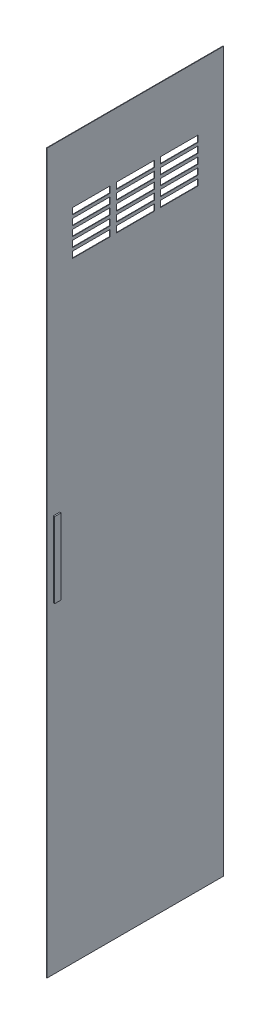
SolidWorks part; units mm, degrees
ref_plane "Front Plane" through (0, 0, 0) normal (0, 0, 1) x (1, 0, 0)
ref_plane "Top Plane" through (0, 0, 0) normal (0, 1, 0) x (1, 0, 0)
ref_plane "Right Plane" through (0, 0, 0) normal (1, 0, 0) x (0, 0, -1)
sketch "Sketch1" plane through (0, 0, 0) normal (1, 0, 0) x (0, 0, -1)
  line L1 (177.8, 725.551) -> (-177.8, 725.551)
  line L2 (177.8, 725.551) -> (177.8, -725.551)
  line L3 (177.8, -725.551) -> (-177.8, -725.551)
  line L4 (-177.8, 725.551) -> (-177.8, -725.551)
  line L5 (177.8, 725.551) -> (-177.8, -725.551) construction
  line L6 (177.8, -725.551) -> (-177.8, 725.551) construction
  point P0 (0, 0)
  dimension "D1" = 355.6
  dimension "D2" = 1451.102
extrude "Boss-Extrude1" add sketch "Sketch1" along normal blind 1 contours L4 L3 L2 L1
sketch "Sketch2" plane through (1, 0, 0) normal (1, 0, 0) x (0, 0, -1)
  line L0 (0, 0) -> (0, 725.551) construction
  line L1 (177.8, 725.551) -> (-177.8, 725.551) construction
  line L2 (0, 362.7755) -> (-177.8, 362.7755) construction
  line L3 (-177.8, 725.551) -> (-177.8, -725.551) construction
  line L4 (0, 362.7755) -> (177.8, 362.7755) construction
  line L5 (177.8, 725.551) -> (177.8, -725.551) construction
  line L6 (0, 725.551) -> (0, 362.7755) construction
  line L7 (-177.8, 725.551) -> (-177.8, 362.7755) construction
  line L8 (-177.8, 544.1632) -> (177.8, 544.1632) construction
  line L9 (177.8, 544.1632) -> (177.8, 725.551) construction
  line L10 (177.8, 725.551) -> (177.8, 634.8571) construction
  line L11 (177.8, 634.8571) -> (-177.8, 634.8571) construction
  line L12 (-177.8, 634.8571) -> (0, 634.8571) construction
  line L13 (0, 634.8571) -> (-88.9, 634.8571) construction
  line L14 (-88.9, 634.8571) -> (-88.9, 544.1632) construction
  line L15 (-88.9, 544.1632) -> (0, 544.1632) construction
  line L16 (0, 544.1632) -> (177.8, 544.1632) construction
  line L17 (177.8, 544.1632) -> (88.9, 544.1632) construction
  line L18 (88.9, 544.1632) -> (88.9, 634.8571) construction
  line L19 (-88.9, 634.8571) -> (0, 544.1632) construction
  line L20 (0, 544.1632) -> (88.9, 634.8571) construction
  line L21 (88.9, 634.8571) -> (177.8, 544.1632) construction
  line L22 (177.8, 544.1632) -> (177.8, 634.8571) construction
  line L23 (177.8, 634.8571) -> (88.9, 544.1632) construction
  line L24 (88.9, 544.1632) -> (0, 634.8571) construction
  line L25 (0, 634.8571) -> (-88.9, 544.1632) construction
  line L26 (-88.9, 544.1632) -> (-177.8, 634.8571) construction
  line L27 (-88.9, 634.8571) -> (-177.8, 544.1632) construction
  line L28 (133.6012, 589.5102) -> (-133.35, 589.5102) construction
  line L30 (-50.5488, 595.7321) -> (-127, 595.7321)
  line L31 (-50.5488, 595.7321) -> (-50.5488, 583.0321)
  line L32 (-50.5488, 583.0321) -> (-127, 583.0321)
  line L33 (-127, 595.7321) -> (-127, 583.0321)
  line L34 (-50.5488, 595.7321) -> (-127, 583.0321) construction
  line L35 (-50.5488, 583.0321) -> (-127, 595.7321) construction
  line L36 (38.4768, 583.1602) -> (-38.2256, 583.1602)
  line L37 (38.4768, 583.1602) -> (38.4768, 595.8602)
  line L38 (38.4768, 595.8602) -> (-38.2256, 595.8602)
  line L39 (-38.2256, 583.1602) -> (-38.2256, 595.8602)
  line L40 (38.4768, 583.1602) -> (-38.2256, 595.8602) construction
  line L41 (38.4768, 595.8602) -> (-38.2256, 583.1602) construction
  line L42 (127.1256, 595.8602) -> (50.6744, 595.8602)
  line L43 (127.1256, 595.8602) -> (127.1256, 583.1602)
  line L44 (127.1256, 583.1602) -> (50.6744, 583.1602)
  line L45 (50.6744, 595.8602) -> (50.6744, 583.1602)
  line L46 (127.1256, 595.8602) -> (50.6744, 583.1602) construction
  line L47 (127.1256, 583.1602) -> (50.6744, 595.8602) construction
  point P28 (-88.7744, 589.3821)
  point P33 (88.9, 589.5102)
  point P36 (0.1256, 589.5102)
  dimension "D1" = 50.8
  dimension "D2" = 12.7
  dimension "D3" = 88.9
extrude "Cut-Extrude1" cut sketch "Sketch2" against normal through all
pattern_linear "LPattern1" count 5 spacing 19.05 along (0, -1, 0) of "Cut-Extrude1"
sketch "Sketch3" plane through (1, 0, 0) normal (1, 0, 0) x (0, 0, -1)
  line L0 (-177.8, 0) -> (177.8, 0) construction
  line L1 (-177.8, 725.551) -> (-177.8, -725.551) construction
  line L2 (177.8, 725.551) -> (177.8, -725.551) construction
  line L3 (-177.8, 76.2) -> (-152.4, 76.2) construction
  line L4 (-152.4, 76.2) -> (-152.4, -76.2) construction
  line L5 (-152.4, -76.2) -> (-177.8, -76.2) construction
  line L6 (-165.1, 76.2) -> (-165.1, -76.2)
  line L7 (-165.1, -76.2) -> (-152.4, -76.2)
  line L8 (-152.4, -76.2) -> (-152.4, 76.2)
  line L9 (-152.4, 76.2) -> (-165.1, 76.2)
  point P8 (-152.4, 0)
  dimension "D1" = 152.4
  dimension "D2" = 25.4
extrude "Boss-Extrude2" add sketch "Sketch3" along normal blind 2.54
